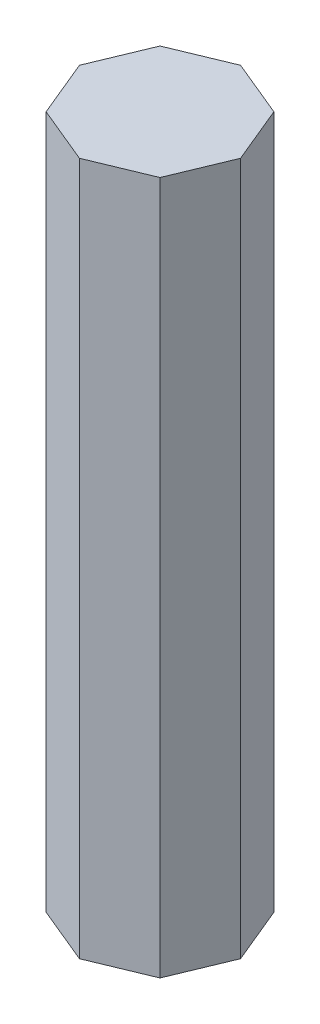
SolidWorks part; units mm, degrees
ref_plane "Front Plane" through (0, 0, 0) normal (0, 0, 1) x (1, 0, 0)
ref_plane "Top Plane" through (0, 0, 0) normal (0, 1, 0) x (1, 0, 0)
ref_plane "Right Plane" through (0, 0, 0) normal (1, 0, 0) x (0, 0, -1)
sketch "Sketch1" plane through (0, 0, 0) normal (0, 1, 0) x (1, 0, 0)
  line L1 (0, 58.0898) -> (-41.0757, 41.0757)
  line L2 (-41.0757, 41.0757) -> (-58.0898, 0)
  line L3 (-58.0898, 0) -> (-41.0757, -41.0757)
  line L4 (-41.0757, -41.0757) -> (0, -58.0898)
  line L5 (0, -58.0898) -> (41.0757, -41.0757)
  line L6 (41.0757, -41.0757) -> (58.0898, 0)
  line L7 (58.0898, 0) -> (41.0757, 41.0757)
  line L8 (41.0757, 41.0757) -> (0, 58.0898)
  circle A0 centre (0, 0) radius 53.668 construction
  dimension "D1" = 44.46
extrude "Boss-Extrude1" add sketch "Sketch1" along normal blind 500
